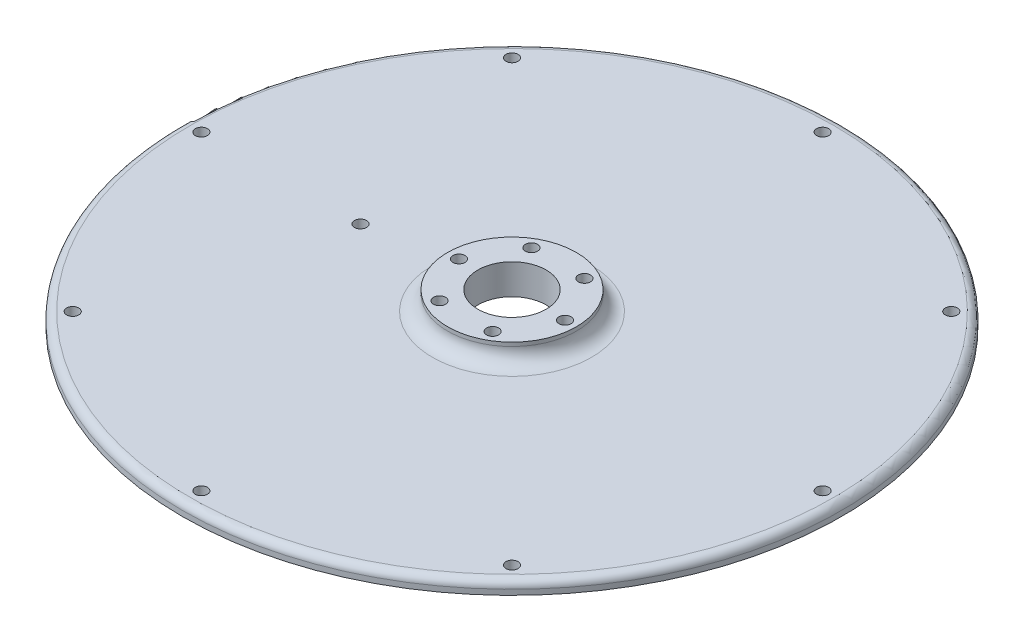
SolidWorks part; units mm, degrees
ref_plane "Front Plane" through (0, 0, 0) normal (0, 0, 1) x (1, 0, 0)
ref_plane "Top Plane" through (0, 0, 0) normal (0, 1, 0) x (1, 0, 0)
ref_plane "Right Plane" through (0, 0, 0) normal (1, 0, 0) x (0, 0, -1)
sketch "Sketch1" plane through (0, 0, 0) normal (0, 0, 1) x (1, 0, 0)
  line L0 (0, 0) -> (0, 139.8559) construction
  line L1 (-365, 0) -> (-385, 0)
  line L2 (-385, 0) -> (-385, 13)
  line L3 (-385, 13) -> (-435, 13)
  line L4 (-435, 13) -> (-435, 20)
  line L5 (-425, 30) -> (-105, 30)
  line L6 (-85, 50) -> (-85, 55)
  line L7 (-85, 55) -> (-45, 55)
  line L8 (-45, 55) -> (-45, 15)
  line L9 (-45, 15) -> (-355, 15)
  line L10 (-365, 5) -> (-365, 0)
  arc A0 (-105, 30) -> (-85, 50) centre (-105, 50) ccw
  arc A1 (-435, 20) -> (-425, 30) centre (-425, 20) cw
  arc A2 (-355, 15) -> (-365, 5) centre (-355, 5) ccw
  dimension "D9" = 20
  dimension "D10" = 10
  dimension "D1" = 870
  dimension "D2" = 90
  dimension "D3" = 170
  dimension "D4" = 770
  dimension "D5" = 20
  dimension "D6" = 15
  dimension "D7" = 15
  dimension "D8" = 40
  dimension "D11" = 2
revolve "Revolve1" add sketch "Sketch1" angle 360 about L0
sketch "Sketch2" plane through (0, 13, 0) normal (0, -1, 0) x (1, 0, 0)
  circle A1 centre (0, 0) radius 410 construction
  circle A2 centre (410, 0) radius 8
  circle A3 centre (289.9138, -289.9138) radius 8
  circle A4 centre (0, -410) radius 8
  circle A5 centre (-289.9138, -289.9138) radius 8
  circle A6 centre (-410, 0) radius 8
  circle A7 centre (-289.9138, 289.9138) radius 8
  circle A8 centre (0, 410) radius 8
  circle A9 centre (289.9138, 289.9138) radius 8
  point P22 (0, 0)
  dimension "D1" = 820
  dimension "D2" = 16
  dimension "D3" = 8
extrude "Cut-Extrude1" cut sketch "Sketch2" against normal through all both
sketch "Sketch3" plane through (0, 55, 0) normal (0, 1, 0) x (1, 0, 0)
  circle A0 centre (0, 0) radius 70 construction
  circle A1 centre (70, 0) radius 8
  circle A2 centre (35, -60.6218) radius 8
  circle A3 centre (-35, -60.6218) radius 8
  circle A4 centre (-70, 0) radius 8
  circle A5 centre (-35, 60.6218) radius 8
  circle A6 centre (35, 60.6218) radius 8
  point P18 (0, 0)
  dimension "D1" = 140
  dimension "D2" = 16
  dimension "D3" = 6
extrude "Cut-Extrude2" cut sketch "Sketch3" against normal blind 20 and the other way through all
sketch "Sketch4" plane through (0, 30, 0) normal (0, 1, 0) x (1, 0, 0)
  line L0 (0, 0) -> (-200, 0) construction
  circle A0 centre (-200, 0) radius 8
  dimension "D1" = 16
  dimension "D2" = 200
extrude "Cut-Extrude3" cut sketch "Sketch4" against normal up to surface (15 mm away) up to face at (0, 15, -45)
sketch "Sketch5" plane through (0, 30, 0) normal (0, 1, 0) x (1, 0, 0)
  line L1 (0, -585.0968) -> (530.1622, -585.0968)
  line L2 (0, -585.0968) -> (0, 592.0726)
  line L3 (0, 592.0726) -> (530.1622, 592.0726)
  line L4 (530.1622, -585.0968) -> (530.1622, 592.0726)
extrude "Cut-Extrude4" [suppressed] cut sketch "Sketch5" against normal through all both and the other way through all
